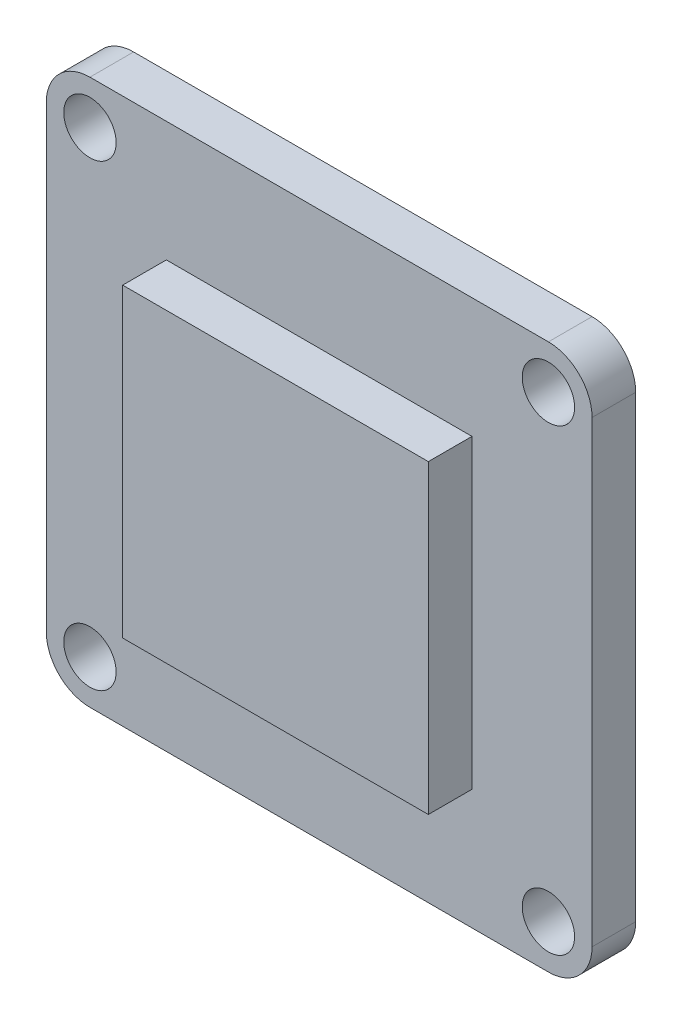
SolidWorks part; units mm, degrees
ref_plane "Front Plane" through (0, 0, 0) normal (0, 0, 1) x (1, 0, 0)
ref_plane "Top Plane" through (0, 0, 0) normal (0, 1, 0) x (1, 0, 0)
ref_plane "Right Plane" through (0, 0, 0) normal (1, 0, 0) x (0, 0, -1)
sketch "Sketch1" plane through (0, 0, 0) normal (0, 0, 1) x (1, 0, 0)
  line L0 (68.5859, -54) -> (68.5859, -29) construction
  line L1 (58.0859, -29) -> (79.0859, -29)
  line L2 (56.0859, -31) -> (56.0859, -52)
  line L3 (58.0859, -54) -> (79.0859, -54)
  line L4 (81.0859, -31) -> (81.0859, -52)
  arc A0 (79.0859, -29) -> (81.0859, -31) centre (79.0859, -31) cw
  arc A1 (79.0859, -54) -> (81.0859, -52) centre (79.0859, -52) ccw
  arc A2 (56.0859, -52) -> (58.0859, -54) centre (58.0859, -52) ccw
  circle A3 centre (58.0859, -52) radius 1.2
  circle A4 centre (79.0859, -52) radius 1.2
  circle A5 centre (79.0859, -31) radius 1.2
  arc A6 (58.0859, -29) -> (56.0859, -31) centre (58.0859, -31) ccw
  circle A7 centre (58.0859, -31) radius 1.2
  point P7 (81.0859, -29)
  point P13 (81.0859, -54)
  point P16 (56.0859, -54)
  dimension "D4" = 2
  dimension "D5" = 2
  dimension "D1" = 12.5
  dimension "D2" = 25
  dimension "D3" = 25
extrude "Boss-Extrude1" add sketch "Sketch1" along normal blind 2
sketch "Sketch2" plane through (0, 0, 2) normal (0, 0, 1) x (1, 0, 0)
  line L0 (56.0859, -41.5) -> (81.0859, -41.5) construction
  line L1 (56.0859, -31) -> (56.0859, -52) construction
  line L2 (81.0859, -52) -> (81.0859, -31) construction
  line L3 (68.5859, -29) -> (68.5859, -54) construction
  line L4 (79.0859, -29) -> (58.0859, -29) construction
  line L5 (58.0859, -54) -> (79.0859, -54) construction
  line L7 (61.5859, -34.5) -> (75.5859, -34.5)
  line L8 (61.5859, -34.5) -> (61.5859, -48.5)
  line L9 (61.5859, -48.5) -> (75.5859, -48.5)
  line L10 (75.5859, -34.5) -> (75.5859, -48.5)
  dimension "D1" = 7
  dimension "D2" = 14
  dimension "D3" = 7
  dimension "D4" = 14
extrude "Boss-Extrude2" add sketch "Sketch2" along normal blind 2
